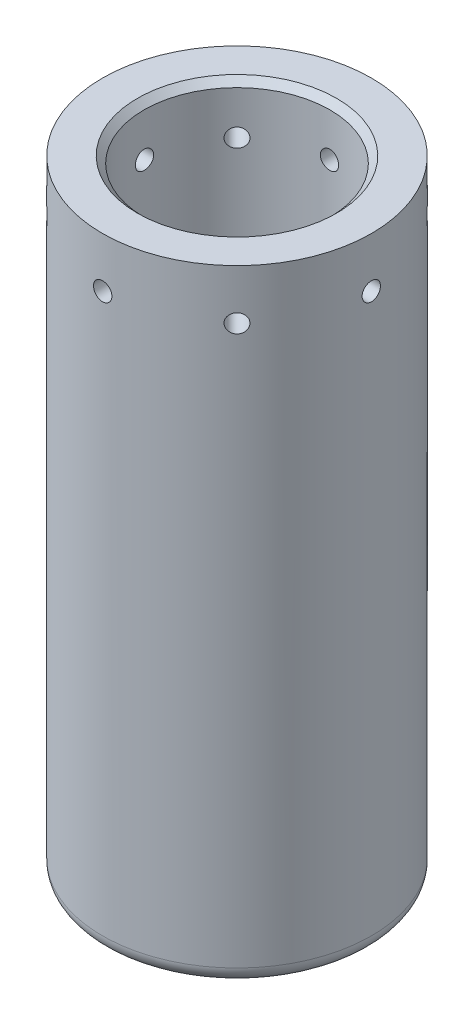
SolidWorks part; units mm, degrees
ref_plane "Front" through (0, 0, 0) normal (0, 0, 1) x (1, 0, 0)
ref_plane "Top" through (0, 0, 0) normal (0, 1, 0) x (1, 0, 0)
ref_plane "Right" through (0, 0, 0) normal (1, 0, 0) x (0, 0, -1)
sketch "Sketch1" plane through (0, 0, 0) normal (0, 1, 0) x (1, 0, 0)
  circle A0 centre (0, 0) radius 16.15
  circle A1 centre (0, 0) radius 11.15
  dimension "D1" = 32.3
  dimension "D2" = 5
extrude "Boss-Extrude1" add sketch "Sketch1" along normal blind 70
sketch "Sketch2" plane through (0, 0, 0) normal (0, -1, 0) x (1, 0, 0)
  circle A1 centre (0, 0) radius 16.15 construction
  circle A2 centre (0, 0) radius 16.15
extrude "Boss-Extrude2" add sketch "Sketch2" along normal blind 5
chamfer "Chamfer1" distance 5 angle 45 1 edges at (0, 0, 11.15)
fillet "Fillet1" radius 2 1 edges at (0, -5, -16.15)
chamfer "Chamfer2" distance 0.8 angle 45 1 edges at (0, 70, 11.15)
ref_plane "Plane1" through (16.15, 0, 0) normal (1, 0, 0) x (0, 0, -1)
sketch "Sketch3" plane through (16.15, 0, 0) normal (1, 0, 0) x (0, 0, -1)
  line L0 (0, 70) -> (0, 51.6689) construction
  line L1 (16.15, 70) -> (-16.15, 70) construction
  circle A0 centre (0, 64) radius 1.1
  dimension "D1" = 2.2
  dimension "D2" = 6
extrude "Cut-Extrude1" cut sketch "Sketch3" against normal blind 10
ref_axis "Axis1" through (0, 69.2, 0) along (0, -1, 0)
pattern_circular "CirPattern1" count 8 over 360 about axis through (0, 69.2, 0) along (0, -1, 0) of "Cut-Extrude1"
